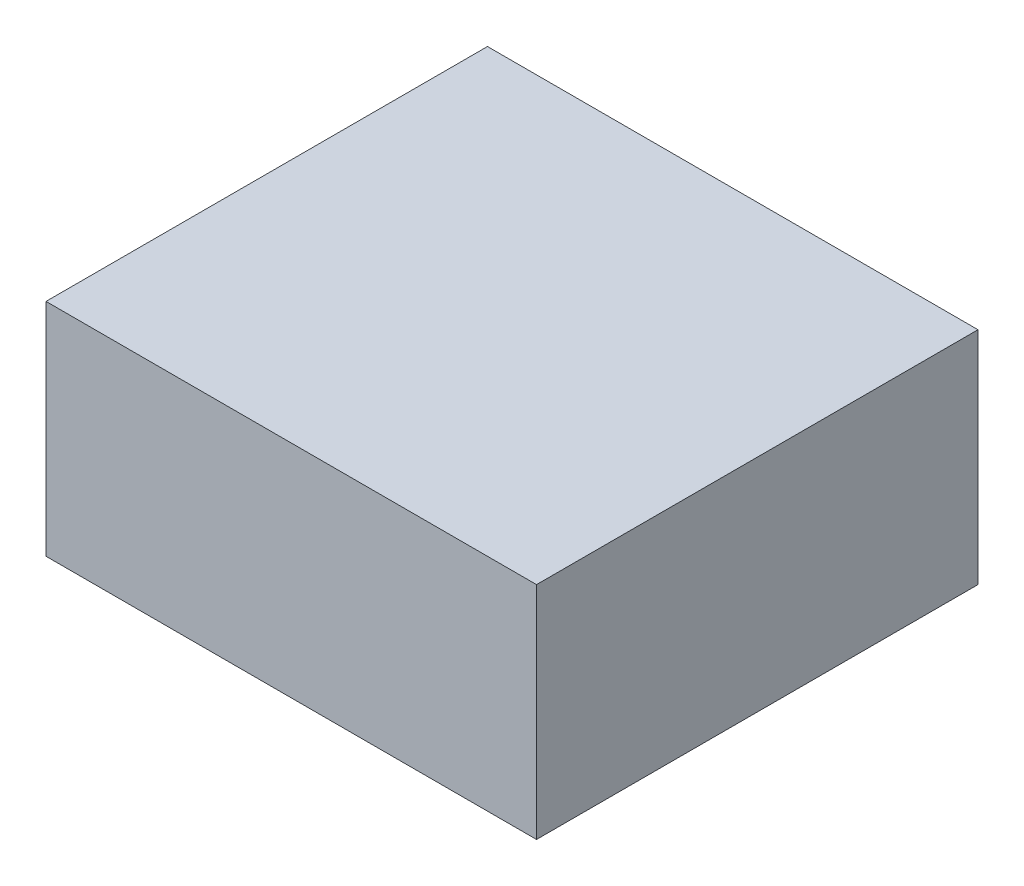
SolidWorks part; units mm, degrees
ref_plane "前基準面" through (0, 0, 0) normal (0, 0, 1) x (1, 0, 0)
ref_plane "上基準面" through (0, 0, 0) normal (0, 1, 0) x (1, 0, 0)
ref_plane "右基準面" through (0, 0, 0) normal (1, 0, 0) x (0, 0, -1)
sketch "草圖1" plane through (0, 0, 0) normal (0, 0, 1) x (1, 0, 0)
  line L1 (-91.3822, 41.895) -> (8.6178, 41.895)
  line L2 (-91.3822, 41.895) -> (-91.3822, -3.105)
  line L3 (-91.3822, -3.105) -> (8.6178, -3.105)
  line L4 (8.6178, 41.895) -> (8.6178, -3.105)
  dimension "D1" = 45
  dimension "D2" = 100
extrude "填料-伸長1" add sketch "草圖1" along normal blind 90
